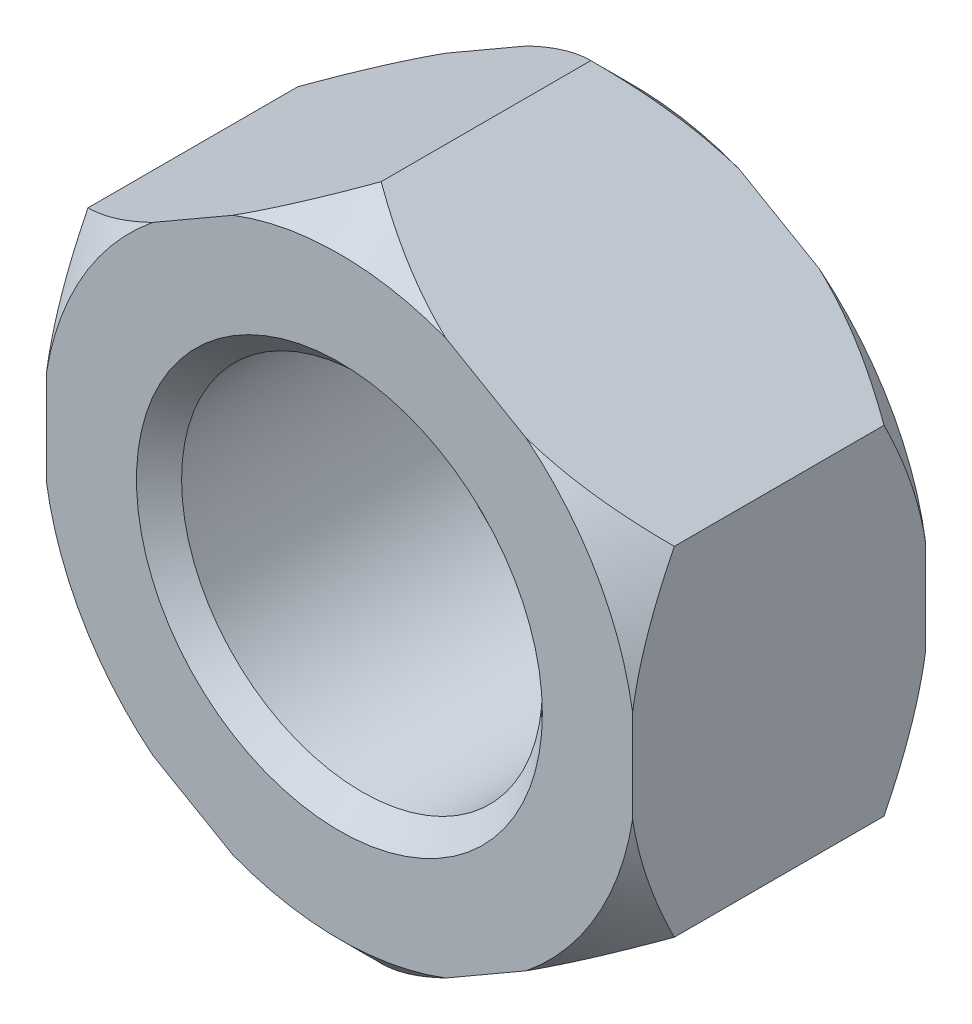
SolidWorks part; units mm, degrees
ref_plane "Спереди" through (0, 0, 0) normal (0, 0, 1) x (1, 0, 0)
ref_plane "Сверху" through (0, 0, 0) normal (0, 1, 0) x (1, 0, 0)
ref_plane "Справа" through (0, 0, 0) normal (1, 0, 0) x (0, 0, -1)
sketch "Эскиз1" plane through (0, 0, 0) normal (0, 0, 1) x (1, 0, 0)
  line L0 (0, 3.7738) -> (0, -4.1898) construction
  line L1 (-3.4469, 0) -> (3.2389, 0) construction
  line L3 (0, 7.5056) -> (-6.5, 3.7528)
  line L4 (-6.5, 3.7528) -> (-6.5, -3.7528)
  line L5 (-6.5, -3.7528) -> (0, -7.5056)
  line L6 (0, -7.5056) -> (6.5, -3.7528)
  line L7 (6.5, -3.7528) -> (6.5, 3.7528)
  line L8 (6.5, 3.7528) -> (0, 7.5056)
  circle A0 centre (0, 0) radius 6.5 construction
extrude "Вытянуть1" add sketch "Эскиз1" along normal blind 6.5
sketch "Эскиз2" plane through (0, 0, 0) normal (0, 0, -1) x (-1, 0, 0)
  circle A0 centre (0, 0) radius 4
ref_axis "Ось4" through (0, 0, 2.6338) along (0, 0, -1)
sketch "Эскиз15" plane through (0, 0, 0) normal (1, 0, 0) x (0, 0, -1)
  line L0 (-6.5, 7.5056) -> (-6.5, 6.5806)
  line L1 (-6.5, 3.7528) -> (-6.5, 7.5056) construction
  line L2 (-6.5, 6.5806) -> (-5.575, 7.5056)
  line L3 (-6.5, 7.5056) -> (0, 7.5056) construction
  line L4 (-5.575, 7.5056) -> (-6.5, 7.5056)
  line L5 (-0.925, 7.5056) -> (0, 7.5056)
  line L6 (0, 7.5056) -> (0, 6.5806)
  line L7 (0, 6.5806) -> (-0.925, 7.5056)
revolve "Вырез-Повернуть1" cut sketch "Эскиз15" angle 360 about axis through (0, 0, 2.6338) along (0, 0, -1)
ref_plane "Плоскость1" through (6.5, 1.0265, 6.5) normal (-0.156, 0.9878, 0) x (-0.9878, -0.156, 0)
extrude "Вырез-Вытянуть1" cut sketch "Эскиз2" against normal through all
chamfer "Фаска1" distance 0.5 angle 45 2 edges at (-4, 0, 0) (-4, 0, 6.5)
